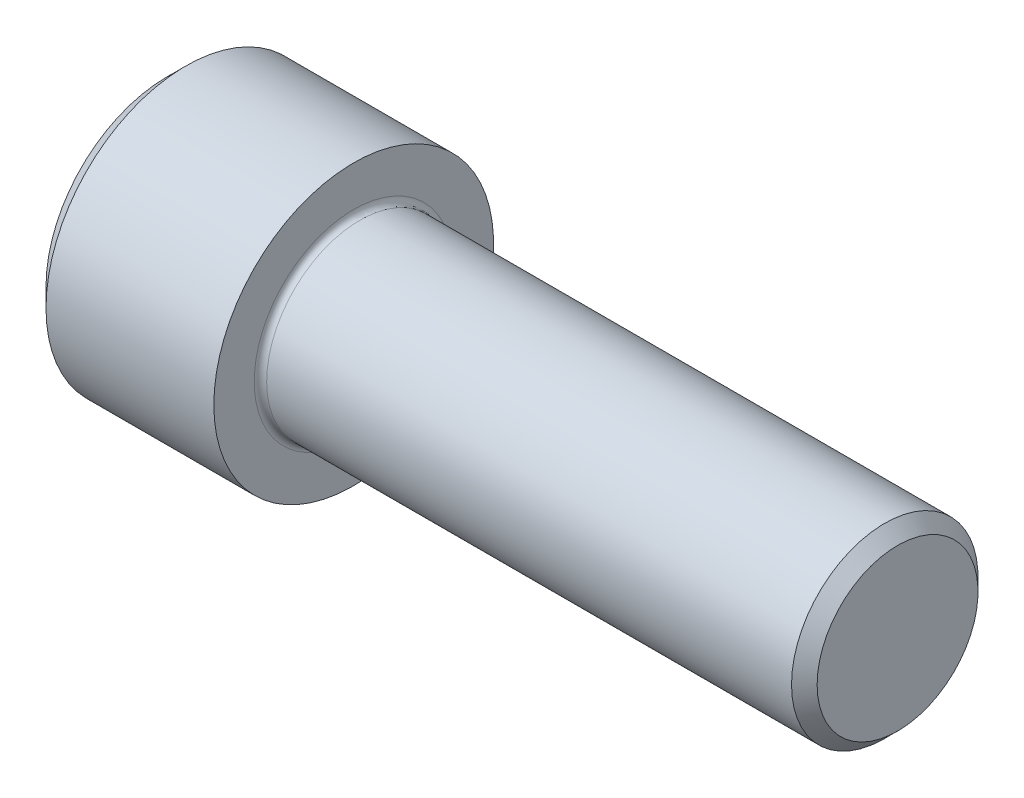
SolidWorks part; units mm, degrees
revolve "Base-Revolve" add sketch "BodySke"
sketch "BodySke" plane through (0, 0, 0) normal (0, 0, 1) x (1, 0, 0)
  line L0 (0, 0) -> (0, 15.6)
  line L1 (2.4, 18) -> (24, 18)
  line L2 (24, 18) -> (24, 12)
  line L3 (24, 12) -> (92.352, 12)
  line L4 (94, 10.352) -> (94, 0)
  line L5 (94, 0) -> (0, 0)
  line L6 (-31.75, 0) -> (127, 0) construction
  line L7 (0, 15.6) -> (2.4, 18)
  line L8 (94, 10.352) -> (92.352, 12)
  line L9 (0, -15.6) -> (2.4, -18) construction
  line L10 (94, -10.352) -> (92.352, -12) construction
  line L11 (27, 9.525) -> (27, 3.175) construction
  line L12 (24, 9.525) -> (24, 3.175) construction
  line L13 (44, 9.525) -> (44, 3.175) construction
  dimension "Diameter" = 24
  dimension "Head_ht" = 24
  dimension "Length" = 70
  dimension "Body_ch_ang" = 45
  dimension "Head_dia" = 36
  dimension "Head_ch_ang" = 45
  dimension "Minor_dia" = 20.704
  dimension "Advance" = 3
  dimension "Thread_nom" = 70
  dimension "Thread_length" = 50
  dimension "Head_ch_ht" = 2.4
cosmetic thread "ThreadCosmetic" [suppressed]
fillet "Fillet1" radius 0.8 1 edges at (24, 0, 12)
ref_plane "Plane1" through (0, 0, 0) normal (0, 0, 1) x (1, 0, 0)
ref_plane "Plane2" through (0, 0, 0) normal (0, 1, 0) x (1, 0, 0)
ref_plane "Plane3" through (0, 0, 0) normal (1, 0, 0) x (0, 0, -1)
other "Configuration Table"
sketch "Sketch2" plane through (0, 0, 0) normal (0, 0, 1) x (1, 0, 0)
  line L0 (0, 9.6375) -> (12, 9.6375)
  line L1 (12, 9.6375) -> (17.5642, 0)
  line L2 (-31.75, 0) -> (127, 0) construction
  line L3 (17.5642, 0) -> (0, 0)
  line L4 (0, 0) -> (0, 9.6375)
  line L5 (0, 15.6) -> (0, -15.6) construction
  line L6 (0, 0) -> (47.625, 0) construction
  line L7 (24, -18) -> (24, 18) construction
  dimension "D1" = 9.6375
  dimension "D2" = 60
revolve "Hex-PreBroach" cut sketch "Sketch2" angle 360 about L6
sketch "Sketch3" plane through (0, 0, 0) normal (-1, 0, 0) x (0, 0.5, 0.866)
  line L0 (5.5642, 9.6375) -> (-5.5642, 9.6375)
  line L1 (-5.5642, 9.6375) -> (-11.1284, 0)
  line L2 (5.5642, 9.6375) -> (11.1284, 0)
  line L3 (5.5642, -9.6375) -> (11.1284, 0)
  line L4 (5.5642, -9.6375) -> (-5.5642, -9.6375)
  line L5 (-5.5642, -9.6375) -> (-11.1284, 0)
  dimension "D1" = 9.6375
  dimension "D2" = 9.6375
  dimension "Hex_size" = 19.275
extrude "Hex" cut sketch "Sketch3" against normal blind 12
sketch "Sketch4" plane through (0, 0, 0) normal (-1, 0, 0) x (0, 0, 1)
  line L0 (0, 0) -> (3.7846, 0)
  line L1 (0, 0) -> (6.1484, 3.5498) construction
  line L2 (0, 0) -> (1.8923, 3.2776)
  line L3 (3.1235, 0.8061) -> (3.6229, 1.0945)
  line L4 (2.2599, 2.3019) -> (2.7593, 2.5903)
  arc A0 (3.1235, 0.8061) -> (2.2599, 2.3019) centre (0, 0) ccw
  arc A1 (3.7846, 0) -> (3.6229, 1.0945) centre (0, 0) ccw
  arc A2 (1.8923, 3.2776) -> (2.7593, 2.5903) centre (0, 0) cw
  dimension "D1" = 30
  dimension "D2" = 60
  dimension "Spline_p_dim" = 1.7272
  dimension "D3" = 0.8636
extrude "Spline" [suppressed] cut sketch "Sketch4" against normal blind 12
pattern_circular "CirPattern1" [suppressed] count 6 every 60
sketch "Sketch5" plane through (0, 0, 0) normal (0, 0, 1) x (1, 0, 0)
  line L0 (-31.75, 0) -> (127, 0) construction
  line L2 (0, 15.6) -> (0, -15.6) construction
  circle A0 centre (7.3, 0) radius 1.075
  dimension "Drilled_hole_dia" = 2.15
  dimension "Drilled_hole_loc" = 7.3
extrude "Hole" [suppressed] cut sketch "Sketch5" against normal through all and the other way through all
pattern_circular "Drilled-4" [suppressed] count 2 every 60
pattern_circular "Drilled-6" [suppressed] count 3 every 60
sketch "ThdSchSke" plane through (0, 0, 0) normal (0, 0, 1) x (1, 0, 0)
  line L0 (27, -10.352) -> (25.8461, -12)
  line L1 (27, -10.352) -> (28.1539, -12)
  line L2 (28.1539, -12) -> (28.1539, -15)
  line L3 (-3.175, 0) -> (5.1513, 0) construction
  line L5 (28.1539, -15) -> (25.8461, -15)
  line L6 (25.8461, -15) -> (25.8461, -12)
  line L7 (0, 15.6) -> (0, -15.6) construction
  dimension "Thread_minor" = 20.704
  dimension "Diameter" = 24
  dimension "Start" = 27
revolve "ThreadSchematic" [suppressed] cut sketch "ThdSchSke" angle 360 about L3
pattern_linear "ThdSchPat" [suppressed]
scale "Scale1" scale about centroid uniform scaling yes scale factor 0.1
equation "\"D2@Sketch3\" = \"Hex_size@Sketch3\" / 2"
equation "\"D1@Sketch3\" = \"Hex_size@Sketch3\" / 2"
equation "\"D1@Sketch2\" = \"Hex_size@Sketch3\" / 2"
equation "\"D3@Sketch4\" = \"Spline_p_dim@Sketch4\" / 2"
equation "\"Thread_minor@ThreadCosmetic\"  =  \"Minor_dia@BodySke\""
equation "\"D2@CirPattern1\" = 360 / \"Num_teeth@CirPattern1\""
equation "\"Wall_thickness@Sketch2\" = \"Head_ht@BodySke\" - \"Key_eng@Hex\""
equation "\"Thread_length@ThreadCosmetic\" = ((sgn( (\"Length@BodySke\" - \"Advance@BodySke\" ) - \"Thread_nom@BodySke\" )-1)*( (\"Length@BodySke\" - \"Advance@BodySke\" ) - \"Thread_nom@BodySke\" ))/-2+ \"Thread_nom@BodySke\""
equation "\"Thread_minor@ThdSchSke\" = \"Minor_dia@BodySke\""
equation "\"Diameter@ThdSchSke\" = \"Diameter@BodySke\""
equation "\"Overcut@ThdSchSke\" = \"Diameter@BodySke\" * 1.25"
equation "\"Start@ThdSchSke\" = \"Head_ht@BodySke\" + \"Length@BodySke\" - \"Thread_length@ThreadCosmetic\"  '---Non-countersunk---"
equation "\"Num_threads@ThdSchPat\" = int( \"Thread_length@ThreadCosmetic\" / \"Advance@BodySke\" + 0.999 )  + 1"
equation "\"Advance@ThdSchPat\" = \"Thread_length@ThreadCosmetic\" /  (\"Num_threads@ThdSchPat\" - 1) 'relax it"
equation "\"Num_threads@ThdSchPat\" = \"Num_threads@ThdSchPat\" - sgn( \"Num_threads@ThdSchPat\" - 1) '---chamfered tips only---"
